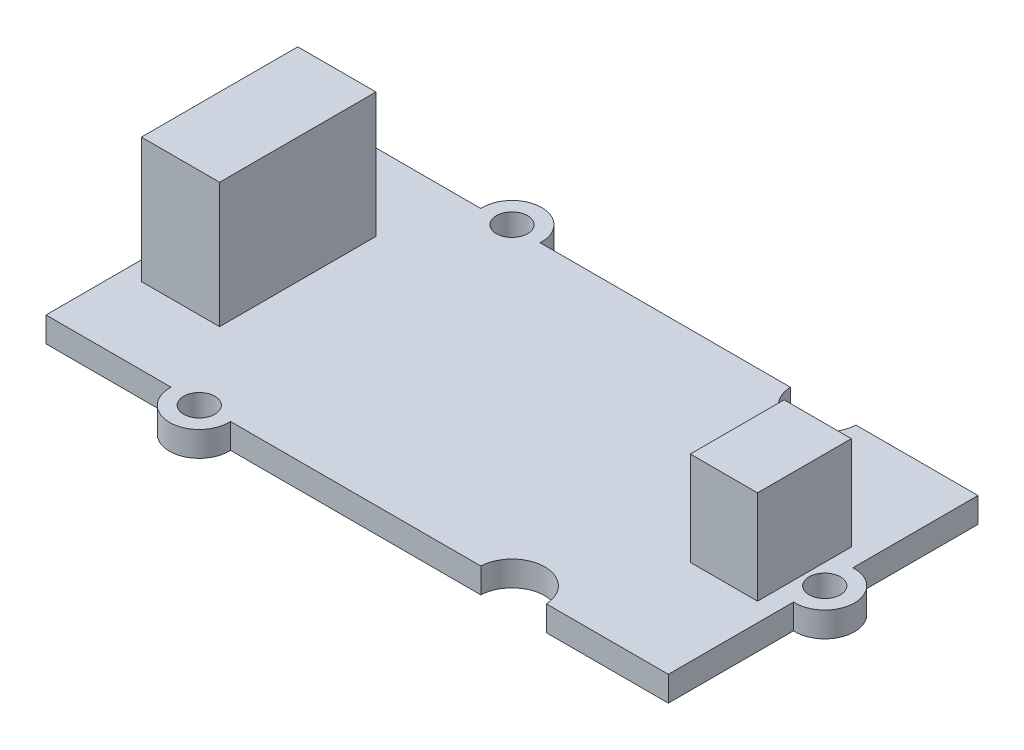
SolidWorks part; units mm, degrees
ref_plane "Płaszczyzna przednia" through (0, 0, 0) normal (0, 0, 1) x (1, 0, 0)
ref_plane "Płaszczyzna górna" through (0, 0, 0) normal (0, 1, 0) x (1, 0, 0)
ref_plane "Płaszczyzna prawa" through (0, 0, 0) normal (1, 0, 0) x (0, 0, -1)
sketch "Sketch1" plane through (0, 0, 0) normal (0, 1, 0) x (1, 0, 0)
  line L1 (-19.9, -9.9) -> (19.9, -9.9)
  line L2 (-19.9, -9.9) -> (-19.9, 9.9)
  line L3 (-19.9, 9.9) -> (19.9, 9.9)
  line L4 (19.9, -9.9) -> (19.9, 9.9)
  line L5 (-19.9, -9.9) -> (19.9, 9.9) construction
  line L6 (-19.9, 9.9) -> (19.9, -9.9) construction
  point P0 (0, 0)
  dimension "D1" = 39.8
  dimension "D2" = 19.8
extrude "Boss-Extrude1" add sketch "Sketch1" along normal blind 1.6
sketch "Sketch2" plane through (0, 0, 0) normal (0, 1, 0) x (1, 0, 0)
  line L0 (0, 0) -> (6.6983, 0) construction
  circle A0 centre (-10, 10) radius 1.9
  circle A1 centre (20, 0) radius 1.9
  circle A2 centre (-10, -10) radius 1.9
  dimension "D1" = 3.8
  dimension "D2" = 10
  dimension "D3" = 20
  dimension "D4" = 10
extrude "Boss-Extrude2" add sketch "Sketch2" along normal up to surface (1.6 mm away) up to face at (0, 1.6, 0)
sketch "Sketch3" plane through (0, 1.6, 0) normal (0, 1, 0) x (1, 0, 0)
  line L0 (0, 0) -> (0, 13.5133) construction
  circle A0 centre (-10, 10) radius 1
  circle A1 centre (-10, -10) radius 1
  circle A2 centre (20, 0) radius 1
  circle A3 centre (-20, 0) radius 1 construction
  circle A4 centre (10, -10) radius 1 construction
  circle A5 centre (10, 10) radius 1 construction
  circle A6 centre (10, 10) radius 2.1
  circle A7 centre (10, -10) radius 2.1
  circle A8 centre (-20, 0) radius 2.1
  dimension "D1" = 2
  dimension "D2" = 4.2
extrude "Cut-Extrude1" cut sketch "Sketch3" against normal up to surface (1.6 mm away) up to face at (0.18, 0, 0)
sketch "Sketch4" plane through (0, 1.6, 0) normal (0, 1, 0) x (1, 0, 0)
  line L0 (19.9, 1.8974) -> (19.9, 9.9) construction
  line L1 (14.4, -3) -> (18.7, -3)
  line L2 (14.4, -3) -> (14.4, 3)
  line L3 (14.4, 3) -> (18.7, 3)
  line L4 (18.7, -3) -> (18.7, 3)
  line L5 (14.4, -3) -> (18.7, 3) construction
  line L6 (14.4, 3) -> (18.7, -3) construction
  point P0 (16.55, 0)
  dimension "D1" = 6
  dimension "D2" = 4.3
  dimension "D3" = 1.2
extrude "Boss-Extrude3" add sketch "Sketch4" along normal blind 6
sketch "Sketch5" plane through (0, 1.6, 0) normal (0, 1, 0) x (1, 0, 0)
  line L0 (-19.9, 9.9) -> (-19.9, 2.0976) construction
  line L1 (-18.7, -5) -> (-13.7, -5)
  line L2 (-18.7, -5) -> (-18.7, 5)
  line L3 (-18.7, 5) -> (-13.7, 5)
  line L4 (-13.7, -5) -> (-13.7, 5)
  line L5 (-18.7, -5) -> (-13.7, 5) construction
  line L6 (-18.7, 5) -> (-13.7, -5) construction
  point P0 (-16.2, 0)
  point P5 (0, 0)
  dimension "D1" = 1.2
  dimension "D2" = 10
  dimension "D3" = 5
extrude "Boss-Extrude4" add sketch "Sketch5" along normal blind 8
